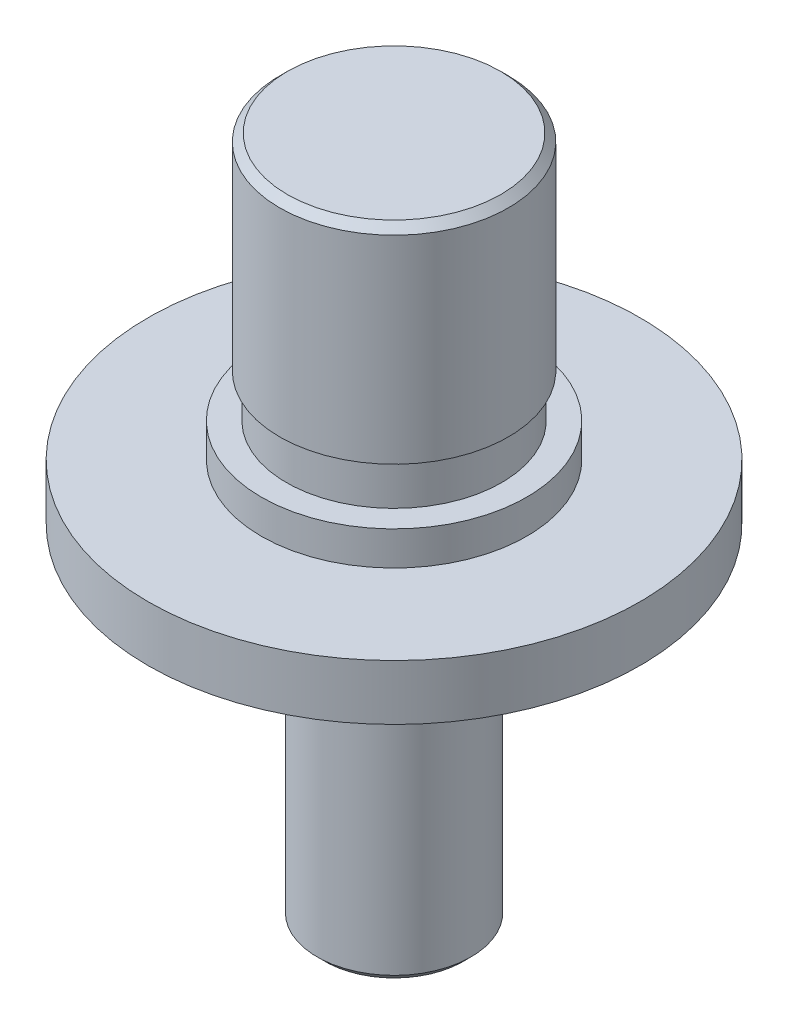
SolidWorks part; units mm, degrees
material "7075-T6 (SN)"
ref_plane "X-Y Datum" through (0, 0, 0) normal (0, 0, 1) x (1, 0, 0)
ref_plane "X-Z Datum" through (0, 0, 0) normal (0, 1, 0) x (1, 0, 0)
ref_plane "Y-Z Datum" through (0, 0, 0) normal (1, 0, 0) x (0, 0, -1)
sketch "Sketch1" plane through (0, 0, 0) normal (1, 0, 0) x (0, 0, -1)
  line L0 (0, 0) -> (-50000, 0) construction
  line L1 (0, 0) -> (0, 50000) construction
  line L2 (0, 0) -> (-27.2547, 0)
  line L3 (-27.2547, 0) -> (-25.0825, -12.319)
  line L4 (-25.0825, -12.319) -> (-25.0825, -17.0815)
  line L5 (-25.0825, -17.0815) -> (-15.875, -17.0815)
  line L8 (0, -71.1505) -> (0, 0)
  line L9 (0, -71.1505) -> (-14.2875, -71.1505)
  line L10 (-15.875, -17.0815) -> (-15.875, -69.563)
  line L11 (-14.2875, -71.1505) -> (-15.875, -69.563)
  dimension "D1" = 12.319
  dimension "D2" = 4.7625
  dimension "D3" = 54.069
  dimension "D4" = 50.165
  dimension "D5" = 45
  dimension "D6" = 80
  dimension "D7" = 31.75
  dimension "D8" = 1.5875
sketch "Sketch2" plane through (0, 0, 0) normal (1, 0, 0) x (0, 0, -1)
  line L0 (0, 0) -> (-52.5, 0)
  line L1 (200000, 0) -> (-250000, 0) construction
  line L2 (-52.5, 0) -> (-52.5, 11.43)
  line L3 (-52.5, 11.43) -> (-27.4096, 11.43)
  line L4 (-27.4096, 11.43) -> (-27.4096, 18.43)
  line L5 (-27.4096, 18.43) -> (-22.225, 18.43)
  line L6 (-22.225, 18.43) -> (-22.225, 27.305)
  line L7 (-22.225, 27.305) -> (-23.6195, 27.305)
  line L10 (0, -200000) -> (0, 250000) construction
  line L11 (0, 69.85) -> (0, 0)
  line L15 (0, 69.85) -> (-22.032, 69.85)
  line L16 (-22.032, 69.85) -> (-23.6195, 68.2625)
  line L17 (-23.6195, 68.2625) -> (-23.6195, 27.305)
  line L18 (0, 0) -> (-50000, 0) construction
  line L19 (0, 0) -> (0, 50000) construction
  line L20 (0, 0) -> (0, -31242.0183) construction
  dimension "D1" = 11.43
  dimension "D2" = 58.42
  dimension "D3" = 47.2389
  dimension "D4" = 1.5875
  dimension "D5" = 45
  dimension "D6" = 54.8192
  dimension "D7" = 105
  dimension "D8" = 7
  dimension "D9" = 40.9575
  dimension "D10" = 44.45
revolve "Bearing Shaft/Flange Support" add sketch "Sketch1" angle 360 about L1
revolve "Drive Pin Support" add sketch "Sketch2" angle 360 about L19
sketch "Sketch5" plane through (0, 0, 0) normal (1, 0, 0) x (0, 0, -1)
  line L0 (0, 69.85) -> (15.875, 69.85)
  line L1 (22.032, 69.85) -> (-22.032, 69.85) construction
  line L4 (15.875, -9.525) -> (0, -9.525)
  line L5 (0, -9.525) -> (0, 69.85)
  line L6 (0, 0) -> (-50000, 0) construction
  line L7 (15.875, -9.525) -> (15.875, 69.85)
  line L8 (0, 0) -> (0, -50000) construction
  dimension "D1" = 79.375
  dimension "D4" = 31.75
revolve "Center Mass Removal" [suppressed] cut sketch "Sketch5" angle 360 about L8
hole_wizard "Drive Pin Holes" [suppressed] positions "Sketch6" profile "Sketch7" tap size "M8x1.25" standard "ANSI Metric"
sketch "Sketch6" plane through (0, 0, 0) normal (0, -1, 0) x (-1, 0, 0)
  circle A0 centre (0, 0) radius 40 construction
  point P0 (0, -40)
  dimension "D1" = 80
sketch "Sketch7" plane through (0, 0, 40) normal (1, 0, 0) x (0, 0, -1)
  line L0 (0, 0) -> (0, 69.85)
  line L1 (0, 69.85) -> (3.4, 69.85)
  line L2 (3.4, 69.85) -> (3.4, 0)
  line L5 (3.4, 0) -> (0, 0)
  line L11 (0, -6.35) -> (0, 107.95) construction
  dimension "Thru Tap Drill Dia." = 6.8
  dimension "Thru Tap Drill Depth" = 69.85
cosmetic thread "Hole Thread1" [suppressed] parameters "D2"=8
pattern_circular "Drive Pin Holes Pattern" [suppressed] count 4 over 360
cosmetic thread "Hole Thread2" [suppressed] parameters "D2"=8
cosmetic thread "Hole Thread3" [suppressed] parameters "D2"=8
cosmetic thread "Hole Thread4" [suppressed] parameters "D2"=8
sketch "Sketch8" [suppressed] plane through (0, 0, 0) normal (0, -1, 0) x (1, 0, 0)
  line L0 (0, 0) -> (-64.0279, 64.0279) construction
  line L1 (0, 0) -> (0, 72.7145) construction
  arc A0 (6.8518, 44.4362) -> (-6.8518, 44.4362) centre (0, 40) ccw
  arc A1 (6.8518, 44.4362) -> (13.2749, 35.4052) centre (113.4583, 113.4583) ccw
  arc A2 (44.4362, -6.8518) -> (44.4362, 6.8518) centre (40, 0) ccw
  arc A3 (44.4362, -6.8518) -> (44.4362, 6.8518) centre (40, 0) ccw
  arc A5 (44.4362, -6.8518) -> (35.4052, -13.2749) centre (113.4583, -113.4583) ccw
  circle A7 centre (0, 40) radius 3.4 construction
  circle A8 centre (0, 0) radius 52.5 construction
  circle A9 centre (0, 0) radius 40 construction
  arc A10 (-6.8518, -44.4362) -> (6.8518, -44.4362) centre (0, -40) ccw
  arc A11 (-6.8518, -44.4362) -> (6.8518, -44.4362) centre (0, -40) ccw
  arc A13 (-44.4362, 6.8518) -> (-44.4362, -6.8518) centre (-40, 0) ccw
  arc A14 (-44.4362, 6.8518) -> (-44.4362, -6.8518) centre (-40, 0) ccw
  arc A15 (-44.4362, 6.8518) -> (-35.4052, 13.2749) centre (-113.4583, 113.4583) ccw
  arc A16 (6.8518, 44.4362) -> (-6.8518, 44.4362) centre (0, 40) ccw
  circle A17 centre (0, 0) radius 52.5
  arc A18 (-6.8518, -44.4362) -> (-13.2749, -35.4052) centre (-113.4583, -113.4583) ccw
  arc A19 (-169.6965, 0.4112) -> (0.4112, -169.6965) centre (-113.4583, -113.4583) ccw
  arc A20 (-13.2749, 35.4052) -> (-35.4052, 13.2749) centre (-22.4506, 22.4506) ccw
  arc A21 (-13.2749, 35.4052) -> (-6.8518, 44.4362) centre (-113.4583, 113.4583) ccw
  arc A22 (35.4052, 13.2749) -> (13.2749, 35.4052) centre (22.4506, 22.4506) ccw
  arc A23 (13.2749, -35.4052) -> (35.4052, -13.2749) centre (22.4506, -22.4506) ccw
  arc A24 (-35.4052, -13.2749) -> (-13.2749, -35.4052) centre (-22.4506, -22.4506) ccw
  arc A25 (35.4052, 13.2749) -> (44.4362, 6.8518) centre (113.4583, 113.4583) ccw
  arc A26 (13.2749, -35.4052) -> (6.8518, -44.4362) centre (113.4583, -113.4583) ccw
  arc A27 (-35.4052, -13.2749) -> (-44.4362, -6.8518) centre (-113.4583, -113.4583) ccw
  point P49 (0, 0)
  circle M10 centre (0, 0) radius 52.5
  dimension "D1" = 4.7625
  dimension "D2" = 45
  dimension "D3" = 254
  dimension "D4" = 80
  dimension "D6" = 31.75
  dimension "D7" = 31.75
  dimension "D5" = 4
  dimension "D8" = 4
extrude "Flange Support Cut" [suppressed] cut sketch "Sketch8" against normal up to next contours A10 A18 A13 A15 A0 A1 A2 A5 M10
sketch "Sketch10" [suppressed] plane through (0, -17.0815, 0) normal (0, -1, 0) x (1, 0, 0)
  line L0 (0, 0) -> (0, 50000) construction
  line L1 (10.6319, -18.415) -> (21.2638, 0)
  line L2 (21.2638, 0) -> (10.6319, 18.415)
  line L3 (10.6319, 18.415) -> (-10.6319, 18.415)
  line L4 (-10.6319, 18.415) -> (-21.2638, 0)
  line L5 (-21.2638, 0) -> (-10.6319, -18.415)
  line L6 (-10.6319, -18.415) -> (10.6319, -18.415)
  line L7 (0, 0) -> (50000, 0) construction
  circle A0 centre (0, 0) radius 18.415 construction
  circle A1 centre (0, 0) radius 25.0825 construction
  circle A2 centre (0, 0) radius 25.0825
  point P17 (0, 18.415)
  dimension "D1" = 36.83
extrude "Brake Hat Hex" [suppressed] cut sketch "Sketch10" against normal blind 4.7625
sketch "Sketch11" plane through (0, -71.1505, 0) normal (0, -1, 0) x (1, 0, 0)
  circle A25 centre (0, 0) radius 9.525 construction
  circle A26 centre (0, 9.525) radius 3.175
  circle A27 centre (8.2489, 4.7625) radius 3.175
  circle A28 centre (8.2489, -4.7625) radius 3.175
  circle A29 centre (0, -9.525) radius 3.175
  circle A30 centre (-8.2489, -4.7625) radius 3.175
  circle A31 centre (-8.2489, 4.7625) radius 3.175
  dimension "D1" = 19.05
  dimension "D2" = 6.35
  dimension "D3" = 6
hole_wizard "5/16 Clearance Hole1" [suppressed] positions "Sketch12" profile "Sketch13" hole size "5/16" standard "ANSI Inch"
sketch "Sketch12" plane through (0, -71.1505, 0) normal (0, -1, 0) x (-1, 0, 0)
  point P0 (0, 0)
sketch "Sketch13" plane through (0, -71.1505, 0) normal (1, 0, 0) x (0, 0, -1)
  line L0 (0, 0) -> (0, 141.0005)
  line L1 (0, 141.0005) -> (4.1021, 141.0005)
  line L2 (4.1021, 141.0005) -> (4.1021, 0)
  line L5 (4.1021, 0) -> (0, 0)
  line L11 (0, -6.35) -> (0, 107.95) construction
  dimension "Thru Hole Dia." = 8.2042
  dimension "Thru Hole Depth" = 141.0005
fillet "Brake Hat Fillet" [suppressed] radius 3.175
fillet "Hub Fillet" [suppressed] radius 0.7937
sketch "Sketch14" plane through (0, 0, 0) normal (1, 0, 0) x (0, 0, -1)
  line L0 (22.032, 69.85) -> (-22.032, 69.85) construction
  line L1 (0, 0) -> (-50000, 0) construction
  line L2 (0, 0) -> (0, -50000) construction
  circle A0 centre (0, 59.05) radius 2
  dimension "D2" = 4
  dimension "D1" = 10.8
extrude "Pin Holes" [suppressed] cut sketch "Sketch14" against normal through all
pattern_circular "Pin Hole Pattern" [suppressed] count 16 over 360
chamfer "Floral Pattern Chamfer" [suppressed] distance 3.175 angle 45
sketch3d "3DSketch2"
  line L0 (0, 0, 0) -> (0, 0, -205.74)
  line L1 (0, 0, -205.74) -> (25.4, 0, -205.74)
  line L2 (0, 0, -205.74) -> (0, -25.4, -205.74)
  dimension "D1" = 25.4
  dimension "D2" = 25.4
  dimension "D3" = 205.74
extrude "Tripod Pins" [suppressed] cut sketch "Sketch11" against normal blind 12.7
fillet "Flange Fillet" [suppressed] radius 1.27
sketch "Sketch15" [suppressed] plane through (0, 0, 0) normal (0, -1, 0) x (1, 0, 0)
  circle A0 centre (0, 0) radius 40 construction
  dimension "D1" = 80
thread "Thread1" [suppressed] pitch 2.1167 start angle 0, offset 0.3048, length 0, pitch 2.1167, diameter 47.625
ref_plane "Plane1" through (-23.8125, 70.1548, 0) normal (0, 0, 1) x (-1, 0, 0)
sketch "Thread Profile1" plane through (-23.8125, 70.1548, 0) normal (0, 0, 1) x (-1, 0, 0)
  line L0 (0, 0) -> (0, 2.1167) construction
  line L11 (0, 0) -> (0, 1.8521)
  line L12 (0, 1.8521) -> (-1.1457, 1.1906)
  line L13 (-1.1457, 1.1906) -> (-1.1457, 0.6615)
  line L15 (-1.1457, 0.6615) -> (0, 0)
  line L17 (-1.1457, 0.926) -> (0, 0.926) construction
  point P2 (0, 0)
  dimension "Pitch" = 2.1167
  dimension "Profile_Angle" = 60
  dimension "Profile_Land" = 0.5292
  dimension "Profile_Height" = 1.1457
fillet "Fillet1" [suppressed] radius 3.175
fillet "Fillet2" [suppressed] radius 3.175
sketch "Sketch16" plane through (0, 11.43, 0) normal (0, 1, 0) x (1, 0, 0)
  circle A0 centre (0, 0) radius 50.8
  circle A1 centre (0, 0) radius 52.5
  dimension "D1" = 101.6
extrude "Cut-Extrude1" cut sketch "Sketch16" against normal up to surface (11.43 mm away) up to face at (0, 0, -27.2547)
